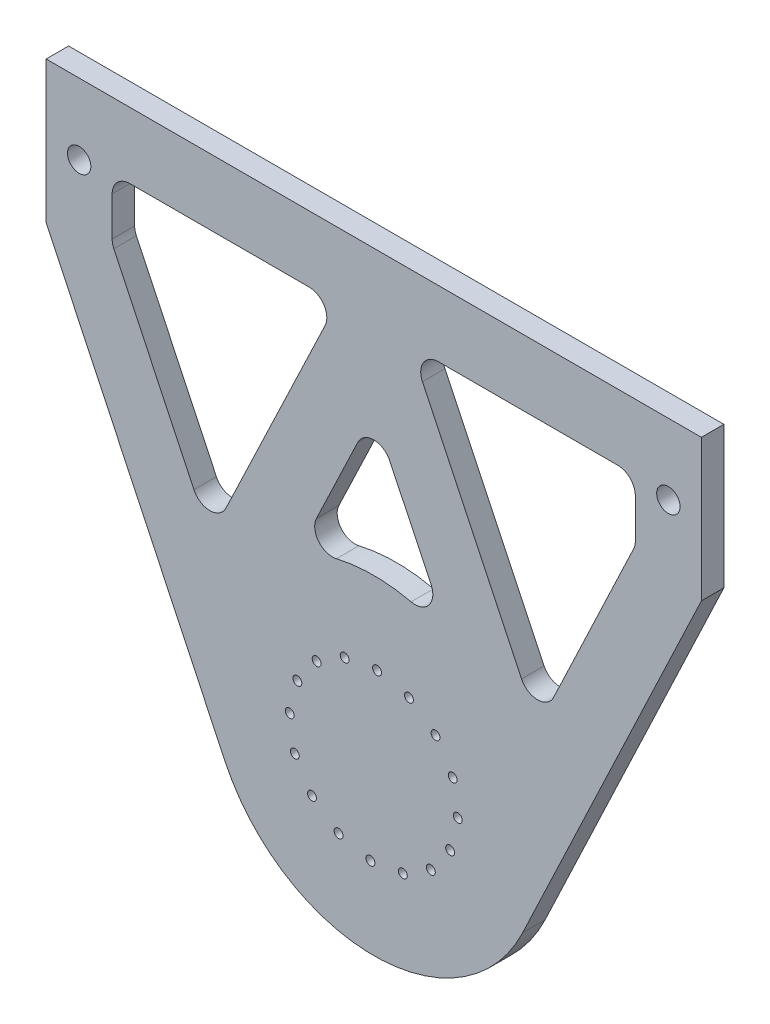
SolidWorks part; units mm, degrees
ref_plane "Front Plane" through (0, 0, 0) normal (0, 0, 1) x (1, 0, 0)
ref_plane "Top Plane" through (0, 0, 0) normal (0, 1, 0) x (1, 0, 0)
ref_plane "Right Plane" through (0, 0, 0) normal (1, 0, 0) x (0, 0, -1)
sketch "Sketch1" plane through (0, 0, 0) normal (0, 0, 1) x (1, 0, 0)
  line L1 (92.5, 126.5) -> (-92.5, 126.5)
  line L3 (0, 0) -> (0, 126.5) construction
  line L4 (-92.5, 126.5) -> (-92.5, 86.5)
  line L5 (-92.5, 86.5) -> (-42.0126, -19.9297)
  line L6 (92.5, 126.5) -> (92.5, 86.5)
  line L7 (92.5, 86.5) -> (42.0126, -19.9297)
  line L8 (42.0126, -19.9297) -> (-42.0126, -19.9297) construction
  circle A0 centre (0, 0) radius 46.5 construction
  arc A1 (-42.0126, -19.9297) -> (42.0126, -19.9297) centre (0, 0) ccw
  dimension "D1" = 93
  dimension "D2" = 185
  dimension "D3" = 126.5
  dimension "D4" = 40
extrude "Boss-Extrude1" add sketch "Sketch1" along normal mid plane 6.35
sketch "Sketch3" plane through (0, 0, -3.175) normal (0, 0, -1) x (-1, 0, 0)
  circle A0 centre (17.4402, -16.1215) radius 1.25 construction
  circle A1 centre (22.282, -8.2203) radius 1.25 construction
  circle A2 centre (9.9432, -21.5684) radius 1.25 construction
  circle A3 centre (0.9324, -23.7317) radius 1.25 construction
  circle A4 centre (-8.2203, -22.282) radius 1.25 construction
  circle A5 centre (-16.1215, -17.4402) radius 1.25 construction
  circle A6 centre (-21.5684, -9.9432) radius 1.25 construction
  circle A7 centre (-23.7317, -0.9324) radius 1.25 construction
  circle A8 centre (-22.282, 8.2203) radius 1.25 construction
  circle A9 centre (-17.4402, 16.1215) radius 1.25 construction
  circle A10 centre (-9.9432, 21.5684) radius 1.25 construction
  circle A11 centre (-0.9324, 23.7317) radius 1.25 construction
  circle A12 centre (8.2203, 22.282) radius 1.25 construction
  circle A13 centre (16.1215, 17.4402) radius 1.25 construction
  circle A14 centre (21.5684, 9.9432) radius 1.25 construction
  circle A15 centre (23.7317, 0.9324) radius 1.25 construction
  circle A16 centre (17.4402, -16.1215) radius 1.25
  circle A17 centre (22.282, -8.2203) radius 1.25
  circle A18 centre (9.9432, -21.5684) radius 1.25
  circle A19 centre (0.9324, -23.7317) radius 1.25
  circle A20 centre (-8.2203, -22.282) radius 1.25
  circle A21 centre (-16.1215, -17.4402) radius 1.25
  circle A22 centre (-21.5684, -9.9432) radius 1.25
  circle A23 centre (-23.7317, -0.9324) radius 1.25
  circle A24 centre (-22.282, 8.2203) radius 1.25
  circle A25 centre (-17.4402, 16.1215) radius 1.25
  circle A26 centre (-9.9432, 21.5684) radius 1.25
  circle A27 centre (-0.9324, 23.7317) radius 1.25
  circle A28 centre (8.2203, 22.282) radius 1.25
  circle A29 centre (16.1215, 17.4402) radius 1.25
  circle A30 centre (21.5684, 9.9432) radius 1.25
  circle A31 centre (23.7317, 0.9324) radius 1.25
extrude "Cut-Extrude2" cut sketch "Sketch3" against normal through all both and the other way through all
sketch "Sketch4" plane through (0, 0, -3.175) normal (0, 0, -1) x (-1, 0, 0)
  line L7 (-41.127, 21.6985) -> (-73.8582, 90.6974)
  line L8 (41.127, 21.6985) -> (73.8582, 90.6974)
  line L12 (25.1698, -11.9399) -> (73.8582, 90.6974)
  line L13 (73.8582, 90.6974) -> (73.8582, 107.8582)
  line L14 (73.8582, 107.8582) -> (-73.8582, 107.8582)
  line L15 (-73.8582, 107.8582) -> (-73.8582, 90.6974)
  line L16 (-73.8582, 90.6974) -> (-25.1698, -11.9399)
  line L17 (25.1698, -11.9399) -> (73.8582, 90.6974) construction
  line L18 (73.8582, 90.6974) -> (73.8582, 107.8582)
  line L19 (73.8582, 107.8582) -> (-73.8582, 107.8582)
  line L20 (-73.8582, 107.8582) -> (-73.8582, 90.6974)
  line L21 (-73.8582, 90.6974) -> (-25.1698, -11.9399) construction
  circle A1 centre (0, 0) radius 46.5 construction
  arc A2 (-25.1698, -11.9399) -> (25.1698, -11.9399) centre (0, 0) ccw
  arc A3 (-25.1698, -11.9399) -> (25.1698, -11.9399) centre (0, 0) ccw construction
  arc A4 (-42.0126, -19.9297) -> (42.0126, -19.9297) centre (0, 0) ccw construction
  arc A5 (-41.127, 21.6985) -> (41.127, 21.6985) centre (0, 0) cw
  dimension "D1" = 18.6418
extrude "Cut-Extrude3" cut sketch "Sketch4" against normal through all both and the other way through all
sketch "Sketch6" plane through (0, 0, 3.175) normal (0, 0, 1) x (1, 0, 0)
  line L0 (-41.127, 21.6985) -> (0, 107.8582) construction
  line L1 (-73.8582, 107.8582) -> (73.8582, 107.8582) construction
  line L2 (0, 107.8582) -> (41.127, 21.6985) construction
  line L3 (-32.7152, 17.6833) -> (0, 86.2207)
  line L4 (0, 86.2207) -> (32.7152, 17.6833)
  line L5 (-49.5387, 25.7137) -> (0, 129.4957) construction
  line L6 (0, 129.4957) -> (49.5387, 25.7137) construction
  line L7 (-49.5387, 25.7137) -> (-32.7152, 17.6833)
  line L8 (32.7152, 17.6833) -> (49.5387, 25.7137)
  line L9 (49.5387, 25.7137) -> (10.3283, 107.8582)
  line L10 (10.3283, 107.8582) -> (-10.3283, 107.8582)
  line L11 (-10.3283, 107.8582) -> (-49.5387, 25.7137)
  dimension "D1" = 9.3209
  dimension "D2" = 9.3209
extrude "Boss-Extrude2" add sketch "Sketch6" against normal up to surface (6.35 mm away) up to face at (0, 77.5516, -3.175)
ref_plane "Plane2" through (0, 86.5, 0) normal (0, 1, 0) x (1, 0, 0)
ref_plane "Plane3" through (0, 106.5, 0) normal (0, 1, 0) x (1, 0, 0)
fillet "Fillet1" radius 5 11 edges at (0, 86.2207, 0) (-21.4668, 41.2483, 0) (21.4668, 41.2483, 0) (-10.3283, 107.8582, 0) (-73.8582, 107.8582, 0) (-73.8582, 90.6974, 0) (73.8582, 90.6974, 0) (73.8582, 107.8582, 0) (10.3283, 107.8582, 0) (46.275, 32.5509, 0) (-46.275, 32.5509, 0)
sketch "Sketch7" plane through (0, 0, 3.175) normal (0, 0, 1) x (1, 0, 0)
  line L0 (-73.8582, 97.3407) -> (-92.5, 97.3407) construction
  line L1 (-73.8582, 91.8232) -> (-73.8582, 102.8582) construction
  line L2 (-92.5, 126.5) -> (-92.5, 86.5) construction
  line L3 (-83.1791, 126.5) -> (-83.1791, 86.5) construction
  line L4 (92.5, 126.5) -> (-92.5, 126.5) construction
  line L5 (0, 0) -> (0, 126.5) construction
  point P10 (-83.1791, 97.3407)
  point P14 (-83.1791, 106.5)
  point P15 (0, 0)
  point P17 (83.1791, 106.5)
hole_wizard "M6 Clearance Hole1" positions "Sketch7" profile "Sketch8" hole size "M6" standard "ANSI Metric" end condition through all
sketch "Sketch8" plane through (83.1791, 106.5, 3.175) normal (1, 0, 0) x (0, -1, 0)
  line L0 (0, 0) -> (0, 6.35)
  line L1 (0, 6.35) -> (3.3, 6.35)
  line L2 (3.3, 6.35) -> (3.3, 0)
  line L5 (3.3, 0) -> (0, 0)
  line L11 (0, -6.35) -> (0, 107.95) construction
  dimension "Thru Hole Dia." = 6.6
  dimension "Thru Hole Depth" = 6.35
